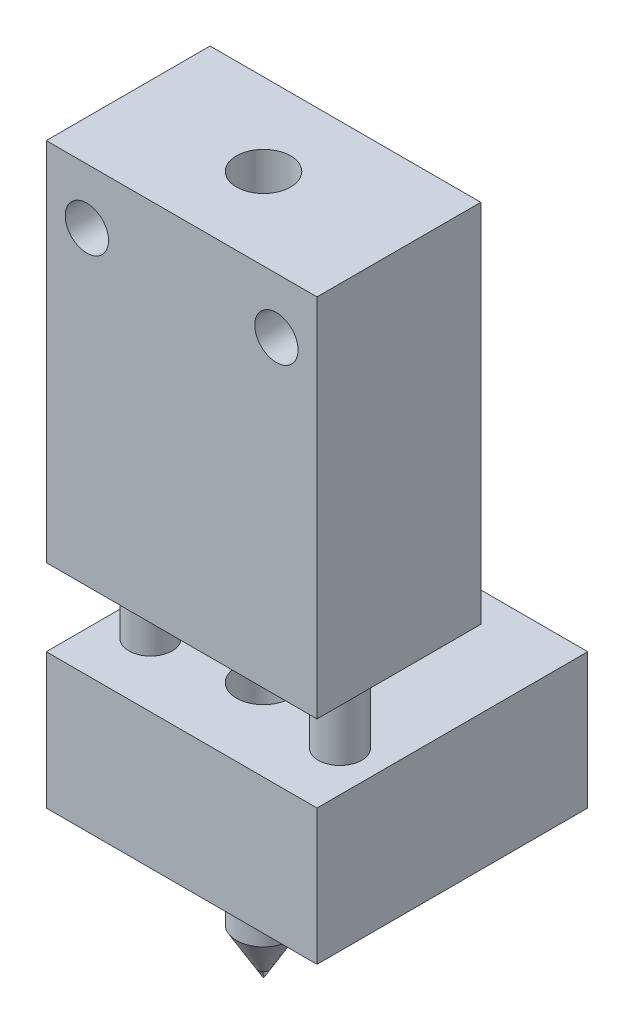
SolidWorks part; units mm, degrees
ref_plane "Front Plane" through (0, 0, 0) normal (0, 0, 1) x (1, 0, 0)
ref_plane "Top Plane" through (0, 0, 0) normal (0, 1, 0) x (1, 0, 0)
ref_plane "Right Plane" through (0, 0, 0) normal (1, 0, 0) x (0, 0, -1)
sketch "Sketch1" plane through (0, 0, 0) normal (0, 0, 1) x (1, 0, 0)
  line L0 (3, 22.9) -> (3, 24.5) construction
  line L1 (0, 0) -> (20, 0)
  line L2 (0, 0) -> (0, 27)
  line L3 (0, 27) -> (20, 27)
  line L4 (20, 0) -> (20, 27)
  line L5 (10, 27) -> (10, 24.5) construction
  circle A0 centre (3, 22.9) radius 1.6
  circle A1 centre (17, 22.9) radius 1.6
  dimension "D4" = 3.2
  dimension "D1" = 20
  dimension "D2" = 27
  dimension "D3" = 14
  dimension "D5" = 2.5
  dimension "D6" = 7
extrude "Boss-Extrude1" add sketch "Sketch1" along normal blind 12.1
sketch "Sketch2" plane through (0, 0, 0) normal (-1, 0, 0) x (0, 0, 1)
  line L0 (12.1, 27) -> (0, 27) construction
  line L1 (12.1, -15.7) -> (-7.9, -15.7)
  line L2 (12.1, -15.7) -> (12.1, -5.7)
  line L3 (12.1, -5.7) -> (-7.9, -5.7)
  line L4 (-7.9, -15.7) -> (-7.9, -5.7)
  line L5 (12.1, 27) -> (12.1, 0) construction
  dimension "D1" = 10
  dimension "D2" = 42.7
  dimension "D3" = 20
extrude "Boss-Extrude2" add sketch "Sketch2" against normal blind 20 separate body
sketch "Sketch3" plane through (0, 0, 0) normal (0, -1, 0) x (1, 0, 0)
  line L0 (20, 12.1) -> (0, 12.1) construction
  line L1 (10, 12.1) -> (10, 10.0639) construction
  circle A0 centre (3, 7.4) radius 1.6
  circle A1 centre (17, 7.4) radius 1.6
  dimension "D2" = 3.2
  dimension "D1" = 4.7
  dimension "D3" = 14
  dimension "D4" = 7
extrude "Boss-Extrude3" add sketch "Sketch3" along normal up to next
sketch "Sketch4" plane through (0, 27, 0) normal (0, 1, 0) x (1, 0, 0)
  line L0 (10, 0) -> (10, -6.3926) construction
  line L1 (20, 0) -> (0, 0) construction
  line L2 (0, -6.05) -> (12.0475, -6.05) construction
  line L3 (0, -12.1) -> (0, 0) construction
  circle A0 centre (10, -6.05) radius 2
  dimension "D1" = 4
extrude "Cut-Extrude1" cut sketch "Sketch4" against normal up to surface (42.7 mm away) up to face at (10, -15.7, 2.1)
sketch "Sketch5" plane through (0, -15.7, 0) normal (0, -1, 0) x (1, 0, 0)
  line L0 (8, 6.05) -> (12, 6.05) construction
  circle A0 centre (10, 6.05) radius 2 construction
ref_plane "Plane1" through (0, 0, 6.05) normal (0, 0, 1) x (1, 0, 0)
sketch "Sketch6" plane through (0, 0, 6.05) normal (0, 0, 1) x (1, 0, 0)
  line L0 (8, -15.7) -> (8, -21.2)
  line L1 (8, -15.7) -> (12, -15.7) construction
  line L2 (12, -15.7) -> (12, -21.2)
  line L3 (20, -15.7) -> (0, -15.7) construction
  line L4 (8, -21.2) -> (10, -24.6)
  line L5 (10, -24.6) -> (12, -21.2)
  line L6 (10, -15.7) -> (10, -33.5) construction
  line L7 (10, -15.7) -> (10, -24.6)
  line L8 (8, -15.7) -> (10, -15.7)
  dimension "D1" = 5.5
  dimension "D2" = 8.9
revolve "Revolve1" add sketch "Sketch6" angle 360 about L7
